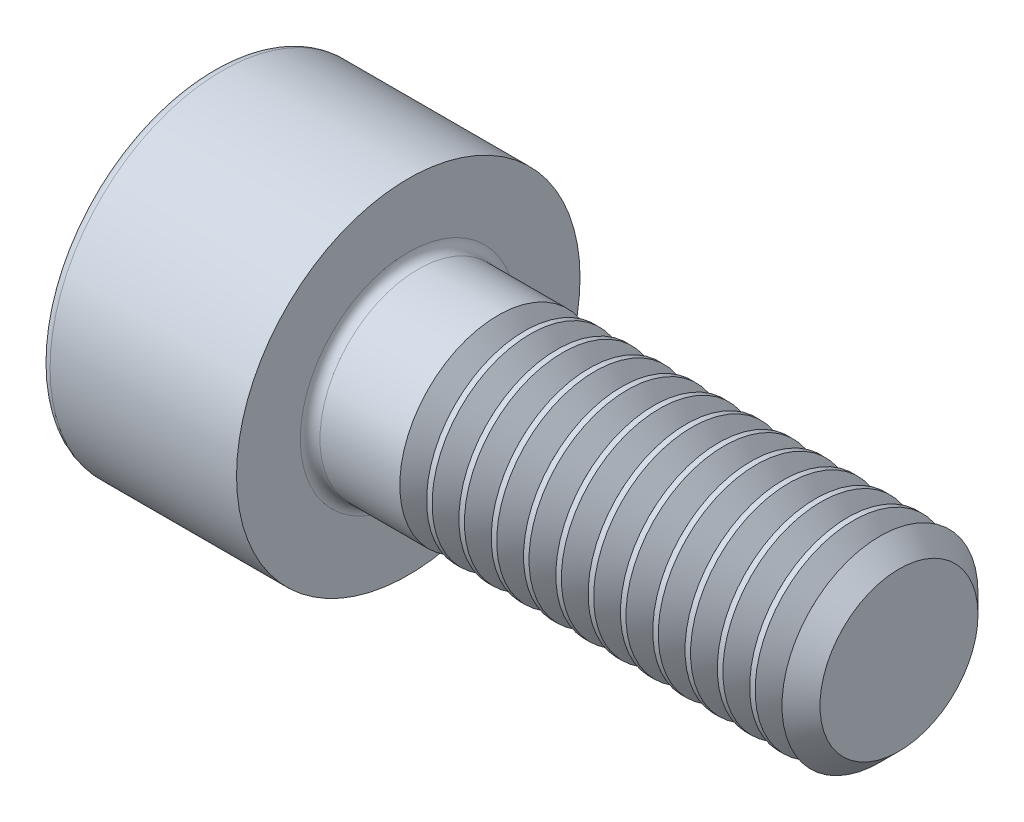
SolidWorks part; units mm, degrees
ref_plane "Front" through (0, 0, 0) normal (0, 0, 1) x (1, 0, 0)
ref_plane "Top" through (0, 0, 0) normal (0, 1, 0) x (1, 0, 0)
ref_plane "Right" through (0, 0, 0) normal (1, 0, 0) x (0, 0, -1)
ref_plane "Plane1" through (0, 0, 0) normal (0, 0, -1) x (-1, 0, 0)
sketch "Sketch1" plane through (0, 0, 0) normal (0, 0, -1) x (-1, 0, 0)
  line L0 (4.6823, 3.6494) -> (4.6823, 0.1494)
  line L1 (4.6823, 0.1494) -> (8.6823, 0.1494)
  line L2 (8.6823, 0.1494) -> (8.6823, 3.6494)
  line L3 (8.6823, 3.6494) -> (4.6823, 3.6494)
  line L4 (4.6823, 0.1494) -> (8.6823, 0.1494) construction
revolve "Revolve1" add sketch "Sketch1" angle 360 about L4
sketch "Sketch2" plane through (-4.6823, 0, 0) normal (1, 0, 0) x (0, 0, -1)
  circle A0 centre (0, 0.1494) radius 2
extrude "Boss-Extrude1" add sketch "Sketch2" along normal blind 1.8269
sketch "Sketch3" plane through (-2.8554, 0, 0) normal (1, 0, 0) x (0, 0, -1)
  circle A0 centre (0, 0.1494) radius 2
extrude "Boss-Extrude2" add sketch "Sketch3" along normal blind 0.2731 draft 55
sketch "Sketch4" plane through (-2.5823, 0, 0) normal (1, 0, 0) x (0, 0, -1)
  circle A0 centre (0, 0.1494) radius 1.61
extrude "Boss-Extrude3" add sketch "Sketch4" along normal blind 0.2731 draft 55 draft outward yes
sketch "Sketch5" plane through (-2.3092, 0, 0) normal (1, 0, 0) x (0, 0, -1)
  circle A0 centre (0, 0.1494) radius 2
extrude "Boss-Extrude4" add sketch "Sketch5" along normal blind 0.1122
sketch "Sketch6" plane through (-2.197, 0, 0) normal (1, 0, 0) x (0, 0, -1)
  circle A0 centre (0, 0.1494) radius 2
extrude "Boss-Extrude5" add sketch "Sketch6" along normal blind 0.2731 draft 55
sketch "Sketch7" plane through (-1.924, 0, 0) normal (1, 0, 0) x (0, 0, -1)
  circle A0 centre (0, 0.1494) radius 1.61
extrude "Boss-Extrude6" add sketch "Sketch7" along normal blind 0.2731 draft 55 draft outward yes
sketch "Sketch8" plane through (-1.6509, 0, 0) normal (1, 0, 0) x (0, 0, -1)
  circle A0 centre (0, 0.1494) radius 2
extrude "Boss-Extrude7" add sketch "Sketch8" along normal blind 0.1122
sketch "Sketch9" plane through (-1.5387, 0, 0) normal (1, 0, 0) x (0, 0, -1)
  circle A0 centre (0, 0.1494) radius 2
extrude "Boss-Extrude8" add sketch "Sketch9" along normal blind 0.2731 draft 55
sketch "Sketch10" plane through (-1.2656, 0, 0) normal (1, 0, 0) x (0, 0, -1)
  circle A0 centre (0, 0.1494) radius 1.61
extrude "Boss-Extrude9" add sketch "Sketch10" along normal blind 0.2731 draft 55 draft outward yes
sketch "Sketch11" plane through (-0.9925, 0, 0) normal (1, 0, 0) x (0, 0, -1)
  circle A0 centre (0, 0.1494) radius 2
extrude "Boss-Extrude10" add sketch "Sketch11" along normal blind 0.1122
sketch "Sketch12" plane through (-0.8804, 0, 0) normal (1, 0, 0) x (0, 0, -1)
  circle A0 centre (0, 0.1494) radius 2
extrude "Boss-Extrude11" add sketch "Sketch12" along normal blind 0.2731 draft 55
sketch "Sketch13" plane through (-0.6073, 0, 0) normal (1, 0, 0) x (0, 0, -1)
  circle A0 centre (0, 0.1494) radius 1.61
extrude "Boss-Extrude12" add sketch "Sketch13" along normal blind 0.2731 draft 55 draft outward yes
sketch "Sketch14" plane through (-0.3342, 0, 0) normal (1, 0, 0) x (0, 0, -1)
  circle A0 centre (0, 0.1494) radius 2
extrude "Boss-Extrude13" add sketch "Sketch14" along normal blind 0.1122
sketch "Sketch15" plane through (-0.222, 0, 0) normal (1, 0, 0) x (0, 0, -1)
  circle A0 centre (0, 0.1494) radius 2
extrude "Boss-Extrude14" add sketch "Sketch15" along normal blind 0.2731 draft 55
sketch "Sketch16" plane through (0.051, 0, 0) normal (1, 0, 0) x (0, 0, -1)
  circle A0 centre (0, 0.1494) radius 1.61
extrude "Boss-Extrude15" add sketch "Sketch16" along normal blind 0.2731 draft 55 draft outward yes
sketch "Sketch17" plane through (0.3241, 0, 0) normal (1, 0, 0) x (0, 0, -1)
  circle A0 centre (0, 0.1494) radius 2
extrude "Boss-Extrude16" add sketch "Sketch17" along normal blind 0.1122
sketch "Sketch18" plane through (0.4363, 0, 0) normal (1, 0, 0) x (0, 0, -1)
  circle A0 centre (0, 0.1494) radius 2
extrude "Boss-Extrude17" add sketch "Sketch18" along normal blind 0.2731 draft 55
sketch "Sketch19" plane through (0.7094, 0, 0) normal (1, 0, 0) x (0, 0, -1)
  circle A0 centre (0, 0.1494) radius 1.61
extrude "Boss-Extrude18" add sketch "Sketch19" along normal blind 0.2731 draft 55 draft outward yes
sketch "Sketch20" plane through (0.9825, 0, 0) normal (1, 0, 0) x (0, 0, -1)
  circle A0 centre (0, 0.1494) radius 2
extrude "Boss-Extrude19" add sketch "Sketch20" along normal blind 0.1122
sketch "Sketch21" plane through (1.0946, 0, 0) normal (1, 0, 0) x (0, 0, -1)
  circle A0 centre (0, 0.1494) radius 2
extrude "Boss-Extrude20" add sketch "Sketch21" along normal blind 0.2731 draft 55
sketch "Sketch22" plane through (1.3677, 0, 0) normal (1, 0, 0) x (0, 0, -1)
  circle A0 centre (0, 0.1494) radius 1.61
extrude "Boss-Extrude21" add sketch "Sketch22" along normal blind 0.2731 draft 55 draft outward yes
sketch "Sketch23" plane through (1.6408, 0, 0) normal (1, 0, 0) x (0, 0, -1)
  circle A0 centre (0, 0.1494) radius 2
extrude "Boss-Extrude22" add sketch "Sketch23" along normal blind 0.1122
sketch "Sketch24" plane through (1.753, 0, 0) normal (1, 0, 0) x (0, 0, -1)
  circle A0 centre (0, 0.1494) radius 2
extrude "Boss-Extrude23" add sketch "Sketch24" along normal blind 0.2731 draft 55
sketch "Sketch25" plane through (2.026, 0, 0) normal (1, 0, 0) x (0, 0, -1)
  circle A0 centre (0, 0.1494) radius 1.61
extrude "Boss-Extrude24" add sketch "Sketch25" along normal blind 0.2731 draft 55 draft outward yes
sketch "Sketch26" plane through (2.2991, 0, 0) normal (1, 0, 0) x (0, 0, -1)
  circle A0 centre (0, 0.1494) radius 2
extrude "Boss-Extrude25" add sketch "Sketch26" along normal blind 0.1122
sketch "Sketch27" plane through (2.4113, 0, 0) normal (1, 0, 0) x (0, 0, -1)
  circle A0 centre (0, 0.1494) radius 2
extrude "Boss-Extrude26" add sketch "Sketch27" along normal blind 0.2731 draft 55
sketch "Sketch28" plane through (2.6844, 0, 0) normal (1, 0, 0) x (0, 0, -1)
  circle A0 centre (0, 0.1494) radius 1.61
extrude "Boss-Extrude27" add sketch "Sketch28" along normal blind 0.2731 draft 55 draft outward yes
sketch "Sketch29" plane through (2.9575, 0, 0) normal (1, 0, 0) x (0, 0, -1)
  circle A0 centre (0, 0.1494) radius 2
extrude "Boss-Extrude28" add sketch "Sketch29" along normal blind 0.1122
sketch "Sketch30" plane through (3.0696, 0, 0) normal (1, 0, 0) x (0, 0, -1)
  circle A0 centre (0, 0.1494) radius 2
extrude "Boss-Extrude29" add sketch "Sketch30" along normal blind 0.2731 draft 55
sketch "Sketch31" plane through (3.3427, 0, 0) normal (1, 0, 0) x (0, 0, -1)
  circle A0 centre (0, 0.1494) radius 1.61
extrude "Boss-Extrude30" add sketch "Sketch31" along normal blind 0.2731 draft 55 draft outward yes
sketch "Sketch32" plane through (3.6158, 0, 0) normal (1, 0, 0) x (0, 0, -1)
  circle A0 centre (0, 0.1494) radius 2
extrude "Boss-Extrude31" add sketch "Sketch32" along normal blind 0.1122
sketch "Sketch33" plane through (3.728, 0, 0) normal (1, 0, 0) x (0, 0, -1)
  circle A0 centre (0, 0.1494) radius 2
extrude "Boss-Extrude32" add sketch "Sketch33" along normal blind 0.2731 draft 55
sketch "Sketch34" plane through (4.001, 0, 0) normal (1, 0, 0) x (0, 0, -1)
  circle A0 centre (0, 0.1494) radius 1.61
extrude "Boss-Extrude33" add sketch "Sketch34" along normal blind 0.2731 draft 55 draft outward yes
sketch "Sketch35" plane through (4.2741, 0, 0) normal (1, 0, 0) x (0, 0, -1)
  circle A0 centre (0, 0.1494) radius 2
extrude "Boss-Extrude34" add sketch "Sketch35" along normal blind 0.1122
sketch "Sketch36" plane through (4.3863, 0, 0) normal (1, 0, 0) x (0, 0, -1)
  circle A0 centre (0, 0.1494) radius 2
extrude "Boss-Extrude35" add sketch "Sketch36" along normal blind 0.2731 draft 55
sketch "Sketch37" plane through (4.6594, 0, 0) normal (1, 0, 0) x (0, 0, -1)
  circle A0 centre (0, 0.1494) radius 1.61
extrude "Boss-Extrude36" add sketch "Sketch37" along normal blind 0.2711 draft 55 draft outward yes
sketch "Sketch38" plane through (4.9305, 0, 0) normal (1, 0, 0) x (0, 0, -1)
  circle A0 centre (0, 0.1494) radius 1.9972
extrude "Boss-Extrude37" add sketch "Sketch38" along normal blind 0.3872 draft 45
sketch "Sketch39" plane through (-8.6823, 0, 0) normal (-1, 0, 0) x (0, 0, 1)
  line L0 (0, -1.6237) -> (1.5355, -0.7371)
  line L1 (1.5355, -0.7371) -> (1.5355, 1.0359)
  line L2 (1.5355, 1.0359) -> (0, 1.9224)
  line L3 (0, 1.9224) -> (-1.5355, 1.0359)
  line L4 (-1.5355, 1.0359) -> (-1.5355, -0.7371)
  line L5 (-1.5355, -0.7371) -> (0, -1.6237)
extrude "Cut-Extrude1" cut sketch "Sketch39" against normal blind 2
sketch "Sketch40" plane through (0, 0, 0) normal (0, 0, 1) x (1, 0, 0)
  line L0 (-6.6823, 1.6849) -> (-6.6823, 0.1494)
  line L1 (-6.6823, 0.1494) -> (-5.7958, 0.1494)
  line L2 (-5.7958, 0.1494) -> (-6.6823, 1.6849)
  line L3 (-6.6823, 0.1494) -> (-5.7958, 0.1494) construction
revolve "Cut-Revolve1" cut sketch "Sketch40" angle 360 about L3
fillet "Fillet1" radius 0.2 2 edges at (-8.6823, 0.1494, 3.5) (-4.6823, 0.1494, -2)
